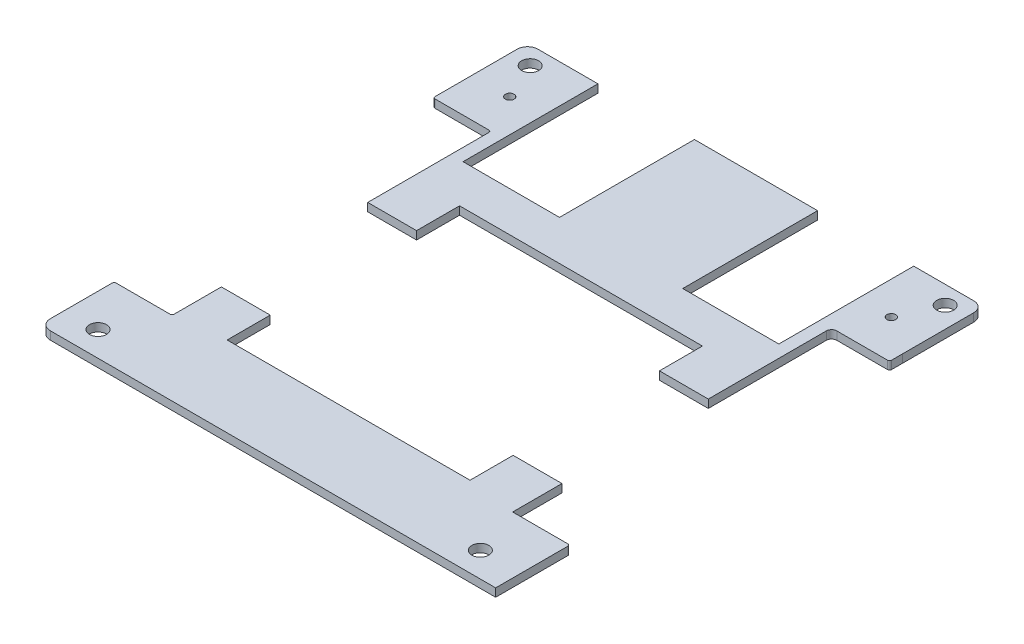
SolidWorks part; units mm, degrees
material "Copper"
ref_plane "Front Plane" through (0, 0, 0) normal (0, 0, 1) x (1, 0, 0)
ref_plane "Top Plane" through (0, 0, 0) normal (0, 1, 0) x (1, 0, 0)
ref_plane "Right Plane" through (0, 0, 0) normal (1, 0, 0) x (0, 0, -1)
sketch "Sketch1" plane through (0, 0, 0) normal (0, 1, 0) x (1, 0, 0)
  line L0 (-44, 45) -> (-44, 29.1624)
  line L1 (-43.6121, 28.7745) -> (-33.2119, 28.7745)
  line L2 (-42, 47) -> (42, 47)
  line L3 (44, 45) -> (44, 31.284)
  line L4 (32.8228, 27.7745) -> (32.8228, -30.4694)
  line L5 (26.2188, 17.9319) -> (-33.6927, 17.9319) construction
  line L6 (33.8228, 28.7745) -> (43.6111, 28.7745)
  line L7 (43.8497, -38.27) -> (43.8497, -47)
  line L8 (42.7059, -47) -> (-42, -47)
  line L9 (-44, -45) -> (-44, -38.977)
  line L10 (-32.824, 28.3866) -> (-32.824, -32.3056)
  line L11 (33.824, -32.6935) -> (36.0988, -32.6935)
  line L12 (23.409, -31.5) -> (-23.409, -31.5)
  line L13 (-23.409, -31.5) -> (-23.409, 13.2954)
  line L14 (-23.409, 13.2954) -> (-12.909, 13.2954)
  line L15 (-12.909, 13.2954) -> (-12.909, 25.9954)
  line L16 (-12.909, 25.9954) -> (12.909, 25.9954)
  line L17 (12.909, 25.9954) -> (12.909, 13.2954)
  line L18 (12.909, 13.2954) -> (23.409, 13.2954)
  line L19 (23.409, 13.2954) -> (23.409, -31.5)
  line L20 (43.8497, -38.27) -> (43.8497, -33.0814)
  line L21 (43.4618, -32.6935) -> (36.0988, -32.6935)
  line L22 (43.8497, -47) -> (42.7059, -47)
  line L23 (-44, 28.7745) -> (52.9697, 28.7745) construction
  line L24 (44, 31.284) -> (43.999, 29.1622)
  line L25 (-33.2119, -32.6935) -> (-36.1, -32.6935)
  line L26 (-44, -38.977) -> (-44, -33.0814)
  line L27 (-43.6121, -32.6935) -> (-36.1, -32.6935)
  line L28 (32.8228, -30.4694) -> (32.8228, -32.6935)
  line L29 (32.8228, -32.6935) -> (33.824, -32.6935)
  circle A0 centre (40, 43.5) radius 1.6383
  circle A1 centre (-40, 43.5) radius 1.6383
  circle A2 centre (-37.6, -42.2) radius 1.6383
  circle A3 centre (36.1, -42.2) radius 1.6383
  arc A5 (-42, 47) -> (-44, 45) centre (-42, 45) ccw
  arc A6 (44, 45) -> (42, 47) centre (42, 45) ccw
  arc A7 (-32.824, -32.3056) -> (-33.2119, -32.6935) centre (-33.2119, -32.3056) cw
  arc A10 (-33.2119, 28.7745) -> (-32.824, 28.3866) centre (-33.2119, 28.3866) cw
  arc A11 (-44, -45) -> (-42, -47) centre (-42, -45) ccw
  arc A12 (-44, 29.1624) -> (-43.6121, 28.7745) centre (-43.6121, 29.1624) ccw
  arc A13 (43.999, 29.1622) -> (43.6111, 28.7745) centre (43.6111, 29.1624) cw
  arc A14 (43.8497, -33.0814) -> (43.4618, -32.6935) centre (43.4618, -33.0814) ccw
  arc A15 (-44, -33.0814) -> (-43.6121, -32.6935) centre (-43.6121, -33.0814) cw
  arc A16 (33.8228, 28.7745) -> (32.8228, 27.7745) centre (33.8228, 27.7745) ccw
  point P27 (32.8228, -32.6935)
  point P51 (-32.824, -32.6935)
  point P54 (-32.824, 28.7745)
  point P60 (43.9988, 28.7745)
  point P67 (32.8228, 28.7745)
  dimension "D24" = 61.468
  dimension "D3" = 80
  dimension "D22" = 1
  dimension "D2" = 6.4
  dimension "D4" = 44.7954
  dimension "D5" = 12.7
  dimension "D6" = 44.7954
  dimension "D7" = 3.5
  dimension "D9" = 4
  dimension "D10" = 3.5
  dimension "D11" = 85.7
  dimension "D12" = 85.7
  dimension "D13" = 21.0046
  dimension "D14" = 11.176
  dimension "D15" = 84
  dimension "D16" = 25.818
  dimension "D17" = 12.7
  dimension "D18" = 46.818
  dimension "D19" = 10.5
  dimension "D20" = 10.5
  dimension "D21" = 73.7
  dimension "D23" = 13.716
  dimension "D26" = 6.604
  dimension "D29" = 11.176
  dimension "D30" = 61.468
  dimension "D31" = 3.276
  dimension "D32" = 3.276
extrude "Boss-Extrude1" add sketch "Sketch1" along normal blind 1.575
sketch "Sketch2" plane through (0, 1.575, 0) normal (0, 1, 0) x (1, 0, 0)
  line L0 (-12.909, 19.06) -> (-30.435, 19.06)
  line L1 (42, 47) -> (-42, 47) construction
  line L2 (-12.909, 25.9954) -> (12.909, 25.9954) construction
  line L3 (-30.435, 47) -> (30.435, 47)
  line L4 (12.909, 13.2954) -> (12.909, 25.9954) construction
  line L5 (12.909, 19.06) -> (30.435, 19.06)
  line L6 (30.435, 19.06) -> (30.435, 47)
  line L7 (0, 47) -> (0, -47) construction
  line L8 (-42, -47) -> (43.8497, -47) construction
  line L9 (-12.909, 25.9954) -> (-12.909, 19.06)
  line L10 (-30.435, 19.06) -> (-30.435, 47)
  line L11 (12.909, 25.9954) -> (12.909, 19.06)
  line L13 (-12.909, 25.9954) -> (12.909, 25.9954)
  dimension "D1" = 27.94
  dimension "D2" = 17.526
extrude "Cut-Extrude1" cut sketch "Sketch2" against normal blind 2.54
sketch "Sketch15" plane through (0, 1.575, 0) normal (0, 1, 0) x (1, 0, 0)
  line L0 (-30.435, 47) -> (-30.435, 19.06) construction
  line L4 (42, 47) -> (30.435, 47) construction
  line L5 (30.435, 19.06) -> (30.435, 47) construction
  circle A0 centre (-36.785, 36.35) radius 0.8382
  circle A1 centre (36.785, 36.332) radius 0.8382
  dimension "D1" = 1.6764
  dimension "D3" = 1.6764
  dimension "D4" = 10.668
  dimension "D2" = 6.35
  dimension "D5" = 6.35
extrude "Cut-Extrude5" cut sketch "Sketch15" against normal blind 1.575
sketch "Sketch16" plane through (0, 1.575, 0) normal (0, 1, 0) x (1, 0, 0)
  line L0 (-42, 47) -> (42, 47) construction
  line L1 (12.909, 19.06) -> (12.909, 13.2954)
  line L2 (12.909, 13.2954) -> (-12.909, 13.2954)
  line L3 (-11.8389, 47) -> (-11.8389, 21)
  line L4 (-30.435, 21) -> (-11.8389, 21)
  line L5 (11.909, 21) -> (11.909, 47)
  line L6 (11.909, 47) -> (-11.8389, 47)
  line L7 (-30.435, 47) -> (-30.435, 19.06) construction
  line L9 (-12.909, 19.06) -> (-12.909, 13.2954)
  line L10 (-30.435, 47) -> (-42, 47) construction
  line L11 (11.909, 21) -> (30.435, 21)
  line L12 (30.435, 19.06) -> (30.435, 47) construction
  line L13 (30.435, 21) -> (30.435, 19.06)
  line L14 (30.435, 19.06) -> (12.909, 19.06)
  line L15 (-30.435, 21) -> (-30.435, 19.06)
  line L16 (-30.435, 19.06) -> (-12.909, 19.06)
  dimension "D1" = 26
extrude "Boss-Extrude2" add sketch "Sketch16" against normal blind 1.575
sketch "Sketch17" plane through (0, 1.575, 0) normal (0, 1, 0) x (1, 0, 0)
  line L2 (-42.6204, -10.5244) -> (-42.6204, -23.1918)
  line L3 (-42.6204, -23.1918) -> (43.1801, -23.1918)
  line L4 (43.1801, -10.5244) -> (43.1801, -23.1918)
  line L6 (-42.6204, -10.5244) -> (-42.6204, 5.0143)
  line L7 (-42.6204, 5.0143) -> (43.1801, 5.0143)
  line L8 (43.1801, -10.5244) -> (43.1801, 5.0143)
extrude "Cut-Extrude7" cut sketch "Sketch17" against normal through all
sketch "Sketch18" plane through (0, 1.575, 0) normal (0, 1, 0) x (1, 0, 0)
  line L1 (33.4307, -29.0671) -> (45.3514, -29.0671)
  line L2 (33.4307, -29.0671) -> (33.4307, -32.653)
  line L3 (33.4307, -32.653) -> (45.3514, -32.653)
  line L4 (45.3514, -29.0671) -> (45.3514, -32.653)
  dimension "D1" = 14.347
  dimension "D2" = 10.419
sketch "Sketch20" plane through (0, 1.575, 0) normal (0, 1, 0) x (1, 0, 0)
